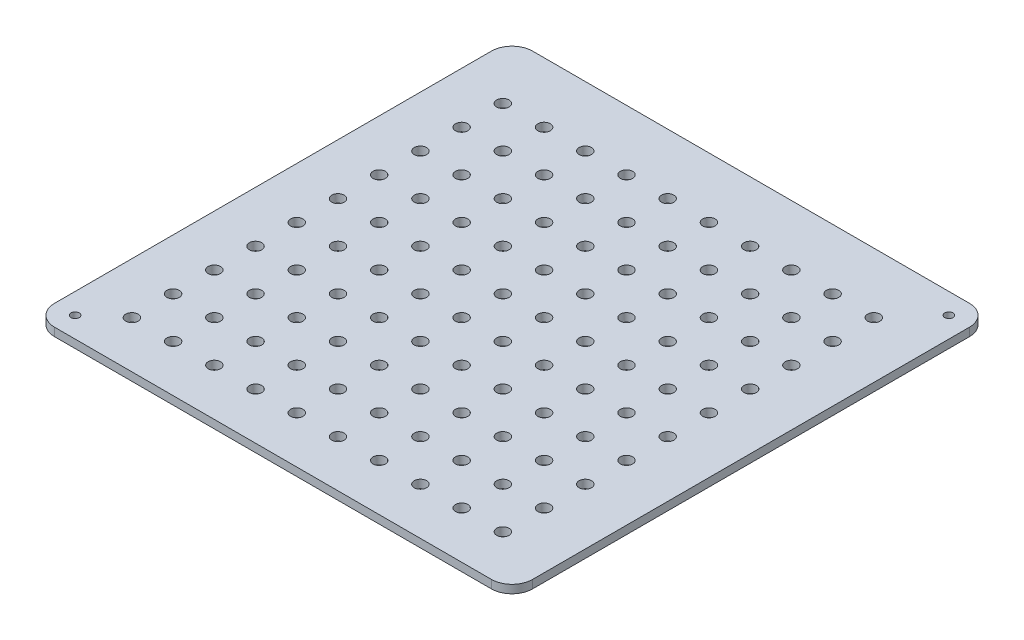
SolidWorks part; units mm, degrees
ref_plane "Front Plane" through (0, 0, 0) normal (0, 0, 1) x (1, 0, 0)
ref_plane "Top Plane" through (0, 0, 0) normal (0, 1, 0) x (1, 0, 0)
ref_plane "Right Plane" through (0, 0, 0) normal (1, 0, 0) x (0, 0, -1)
sketch "Sketch1" plane through (0, 0, 0) normal (0, 1, 0) x (1, 0, 0)
  line L1 (53, 58) -> (-53, 58)
  line L2 (58, 53) -> (58, -53)
  line L3 (53, -58) -> (-53, -58)
  line L4 (-58, 53) -> (-58, -53)
  line L5 (58, 58) -> (-58, -58) construction
  line L6 (58, -58) -> (-58, 58) construction
  arc A0 (-53, 58) -> (-58, 53) centre (-53, 53) ccw
  arc A1 (58, -53) -> (53, -58) centre (53, -53) cw
  arc A2 (53, 58) -> (58, 53) centre (53, 53) cw
  arc A3 (-53, -58) -> (-58, -53) centre (-53, -53) cw
  point P0 (0, 0)
  dimension "D3" = 5
  dimension "D1" = 116
  dimension "D2" = 116
extrude "Boss-Extrude1" add sketch "Sketch1" along normal blind 2
sketch "Sketch2" plane through (0, 2, 0) normal (0, 1, 0) x (1, 0, 0)
  circle A0 centre (-45.6049, 43.3863) radius 1.5
  circle A1 centre (-35.6049, 43.3863) radius 1.5
  circle A2 centre (-25.6049, 43.3863) radius 1.5
  circle A3 centre (-15.6049, 43.3863) radius 1.5
  circle A4 centre (-5.6049, 43.3863) radius 1.5
  circle A5 centre (4.3951, 43.3863) radius 1.5
  circle A6 centre (14.3951, 43.3863) radius 1.5
  circle A7 centre (24.3951, 43.3863) radius 1.5
  circle A8 centre (34.3951, 43.3863) radius 1.5
  circle A9 centre (44.3951, 43.3863) radius 1.5
  circle A10 centre (-35.6049, 33.3863) radius 1.5
  circle A11 centre (-25.6049, 33.3863) radius 1.5
  circle A12 centre (-15.6049, 33.3863) radius 1.5
  circle A13 centre (-5.6049, 33.3863) radius 1.5
  circle A14 centre (4.3951, 33.3863) radius 1.5
  circle A15 centre (14.3951, 33.3863) radius 1.5
  circle A16 centre (24.3951, 33.3863) radius 1.5
  circle A17 centre (34.3951, 33.3863) radius 1.5
  circle A18 centre (44.3951, 33.3863) radius 1.5
  circle A19 centre (-35.6049, 23.3863) radius 1.5
  circle A20 centre (-25.6049, 23.3863) radius 1.5
  circle A21 centre (-15.6049, 23.3863) radius 1.5
  circle A22 centre (-5.6049, 23.3863) radius 1.5
  circle A23 centre (4.3951, 23.3863) radius 1.5
  circle A24 centre (14.3951, 23.3863) radius 1.5
  circle A25 centre (24.3951, 23.3863) radius 1.5
  circle A26 centre (34.3951, 23.3863) radius 1.5
  circle A27 centre (44.3951, 23.3863) radius 1.5
  circle A28 centre (-35.6049, 13.3863) radius 1.5
  circle A29 centre (-25.6049, 13.3863) radius 1.5
  circle A30 centre (-15.6049, 13.3863) radius 1.5
  circle A31 centre (-5.6049, 13.3863) radius 1.5
  circle A32 centre (4.3951, 13.3863) radius 1.5
  circle A33 centre (14.3951, 13.3863) radius 1.5
  circle A34 centre (24.3951, 13.3863) radius 1.5
  circle A35 centre (34.3951, 13.3863) radius 1.5
  circle A36 centre (44.3951, 13.3863) radius 1.5
  circle A37 centre (-35.6049, 3.3863) radius 1.5
  circle A38 centre (-25.6049, 3.3863) radius 1.5
  circle A39 centre (-15.6049, 3.3863) radius 1.5
  circle A40 centre (-5.6049, 3.3863) radius 1.5
  circle A41 centre (4.3951, 3.3863) radius 1.5
  circle A42 centre (14.3951, 3.3863) radius 1.5
  circle A43 centre (24.3951, 3.3863) radius 1.5
  circle A44 centre (34.3951, 3.3863) radius 1.5
  circle A45 centre (44.3951, 3.3863) radius 1.5
  circle A46 centre (-35.6049, -6.6137) radius 1.5
  circle A47 centre (-25.6049, -6.6137) radius 1.5
  circle A48 centre (-15.6049, -6.6137) radius 1.5
  circle A49 centre (-5.6049, -6.6137) radius 1.5
  circle A50 centre (4.3951, -6.6137) radius 1.5
  circle A51 centre (14.3951, -6.6137) radius 1.5
  circle A52 centre (24.3951, -6.6137) radius 1.5
  circle A53 centre (34.3951, -6.6137) radius 1.5
  circle A54 centre (44.3951, -6.6137) radius 1.5
  circle A55 centre (-35.6049, -16.6137) radius 1.5
  circle A56 centre (-25.6049, -16.6137) radius 1.5
  circle A57 centre (-15.6049, -16.6137) radius 1.5
  circle A58 centre (-5.6049, -16.6137) radius 1.5
  circle A59 centre (4.3951, -16.6137) radius 1.5
  circle A60 centre (14.3951, -16.6137) radius 1.5
  circle A61 centre (24.3951, -16.6137) radius 1.5
  circle A62 centre (34.3951, -16.6137) radius 1.5
  circle A63 centre (44.3951, -16.6137) radius 1.5
  circle A64 centre (-35.6049, -26.6137) radius 1.5
  circle A65 centre (-25.6049, -26.6137) radius 1.5
  circle A66 centre (-15.6049, -26.6137) radius 1.5
  circle A67 centre (-5.6049, -26.6137) radius 1.5
  circle A68 centre (4.3951, -26.6137) radius 1.5
  circle A69 centre (14.3951, -26.6137) radius 1.5
  circle A70 centre (24.3951, -26.6137) radius 1.5
  circle A71 centre (34.3951, -26.6137) radius 1.5
  circle A72 centre (44.3951, -26.6137) radius 1.5
  circle A73 centre (-35.6049, -36.6137) radius 1.5
  circle A74 centre (-25.6049, -36.6137) radius 1.5
  circle A75 centre (-15.6049, -36.6137) radius 1.5
  circle A76 centre (-5.6049, -36.6137) radius 1.5
  circle A77 centre (4.3951, -36.6137) radius 1.5
  circle A78 centre (14.3951, -36.6137) radius 1.5
  circle A79 centre (24.3951, -36.6137) radius 1.5
  circle A80 centre (34.3951, -36.6137) radius 1.5
  circle A81 centre (44.3951, -36.6137) radius 1.5
  circle A82 centre (-35.6049, -46.6137) radius 1.5
  circle A83 centre (-25.6049, -46.6137) radius 1.5
  circle A84 centre (-15.6049, -46.6137) radius 1.5
  circle A85 centre (-5.6049, -46.6137) radius 1.5
  circle A86 centre (4.3951, -46.6137) radius 1.5
  circle A87 centre (14.3951, -46.6137) radius 1.5
  circle A88 centre (24.3951, -46.6137) radius 1.5
  circle A89 centre (34.3951, -46.6137) radius 1.5
  circle A90 centre (44.3951, -46.6137) radius 1.5
  circle A91 centre (-45.6049, 33.3863) radius 1.5
  circle A92 centre (-45.6049, 23.3863) radius 1.5
  circle A93 centre (-45.6049, 13.3863) radius 1.5
  circle A94 centre (-45.6049, 3.3863) radius 1.5
  circle A95 centre (-45.6049, -6.6137) radius 1.5
  circle A96 centre (-45.6049, -16.6137) radius 1.5
  circle A97 centre (-45.6049, -26.6137) radius 1.5
  circle A98 centre (-45.6049, -36.6137) radius 1.5
  circle A99 centre (-45.6049, -46.6137) radius 1.5
  dimension "D1" = 3
  dimension "D2" = 10
  dimension "D3" = 10
extrude "Cut-Extrude1" cut sketch "Sketch2" against normal through all
sketch "Sketch3" plane through (0, 0, 0) normal (0, -1, 0) x (1, 0, 0)
  line L0 (58, 53) -> (58, -53) construction
  line L1 (53, -58) -> (-53, -58) construction
  line L2 (-53, 58) -> (53, 58) construction
  line L3 (-58, -53) -> (-58, 53) construction
  circle A0 centre (-53, 53) radius 1
  circle A1 centre (53, -53) radius 1
  dimension "D1" = 2
  dimension "D2" = 2
  dimension "D3" = 5
  dimension "D4" = 5
  dimension "D5" = 5
  dimension "D6" = 5
extrude "Cut-Extrude2" cut sketch "Sketch3" against normal through all
